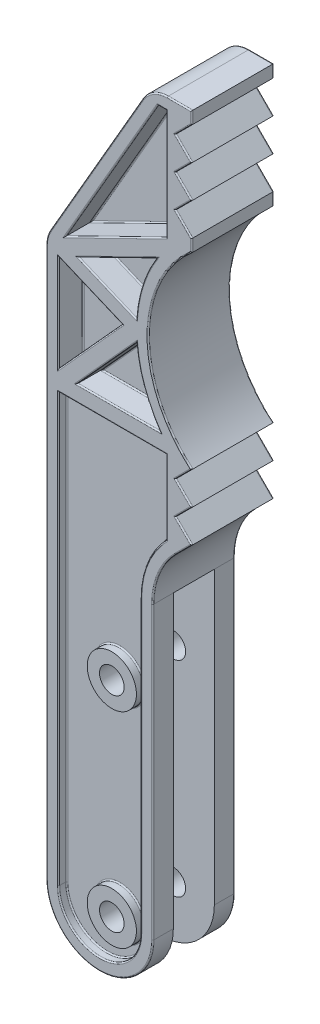
SolidWorks part; units mm, degrees
material "AISI 1020"
ref_plane "Front Plane" through (0, 0, 0) normal (0, 0, 1) x (1, 0, 0)
ref_plane "Top Plane" through (0, 0, 0) normal (0, 1, 0) x (1, 0, 0)
ref_plane "Right Plane" through (0, 0, 0) normal (1, 0, 0) x (0, 0, -1)
sketch "Sketch1" plane through (0, 0, 0) normal (0, 0, 1) x (1, 0, 0)
  line L0 (0, 0) -> (0, 90) construction
  line L1 (0, 90) -> (-5, 90) construction
  line L2 (-5, 90) -> (-17.75, 67.9164) construction
  line L3 (-17.75, 67.9164) -> (-17.75, 0) construction
  line L4 (-17.75, 0) -> (0, 0) construction
  line L5 (-2, 90) -> (-2, 75) construction
  line L6 (-2, 75) -> (0, 75) construction
  line L7 (0, 88.5) -> (-2, 86.5)
  line L8 (-2, 86.5) -> (0, 84.5)
  line L9 (0, 84.5) -> (-2, 82.5)
  line L10 (-2, 82.5) -> (0, 80.5)
  line L11 (0, 80.5) -> (-2, 78.5)
  line L12 (-2, 78.5) -> (0, 76.5)
  line L13 (-17.75, 64.3) -> (0, 64.3) construction
  line L14 (-9.75, 0) -> (-9.75, 25) construction
  line L15 (-2, 42.1) -> (0, 44.1)
  line L16 (0, 44.1) -> (-2, 46.1)
  line L17 (-2, 46.1) -> (0, 48.1)
  line L18 (0, 48.1) -> (-2, 50.1)
  line L19 (-2, 50.1) -> (0, 52.1)
  line L20 (0, 88.5) -> (0, 90)
  line L21 (0, 90) -> (-5, 90)
  line L22 (0, 76.5) -> (0, 75)
  line L23 (-5, 90) -> (-17.75, 67.9164)
  line L24 (-17.75, 67.9164) -> (-17.75, 0)
  line L25 (-4.75, 0) -> (-4.75, 35.4609)
  arc A0 (0, 75) -> (0, 52.1) centre (9.6901, 63.55) ccw
  arc A1 (-17.75, 0) -> (-4.75, 0) centre (-11.25, 0) ccw
  arc A2 (-2, 42.1) -> (-4.75, 35.4609) centre (4.6391, 35.4609) ccw
  circle A3 centre (-9.75, 0) radius 1.5
  circle A4 centre (-9.75, 25) radius 1.5
  dimension "D11" = 15
  dimension "D12" = 6.5
  dimension "D13" = 3
  dimension "D1" = 90
  dimension "D2" = 30
  dimension "D3" = 5
  dimension "D4" = 17.75
  dimension "D5" = 2
  dimension "D6" = 15
  dimension "D7" = 1.5
  dimension "D8" = 3.5
  dimension "D10" = 24.2
  dimension "D14" = 5
  dimension "D15" = 25
  dimension "D9" = 3
extrude "Boss-Extrude1" add sketch "Sketch1" along normal mid plane 10
sketch "Sketch2" plane through (0, 0, 0) normal (0, 0, 1) x (1, 0, 0)
  line L0 (-15, -8.4108) -> (-15, 23.5892)
  line L1 (-4.75, 0) -> (-4.75, 35.4609) construction
  line L2 (-4.75, 0) -> (-4.75, -8.4108)
  line L3 (-4.75, -8.4108) -> (-15, -8.4108)
  line L4 (-4.75, 0) -> (-4.75, 35.4609)
  arc A0 (-15, 23.5892) -> (-4.75, 35.4609) centre (-3, 23.5892) cw
  dimension "D2" = 12
  dimension "D1" = 10.25
  dimension "D3" = 32
extrude "Cut-Extrude1" cut sketch "Sketch2" against normal mid plane 5
sketch "Sketch3" plane through (0, 0, 5) normal (0, 0, 1) x (1, 0, 0)
  line L0 (-3.1276, 88.5) -> (-3.1276, 43.0931)
  line L34 (-2.1213, 88.5) -> (-4.134, 88.5)
  line L35 (-4.134, 88.5) -> (-16.25, 67.5144)
  line L36 (-16.25, 67.5144) -> (-16.25, 0)
  line L37 (-6.25, 0) -> (-6.25, 35.4609)
  line L38 (-3.0607, 43.1607) -> (-2.1213, 44.1)
  line L39 (-2.1213, 44.1) -> (-4.1213, 46.1)
  line L40 (-4.1213, 46.1) -> (-2.1213, 48.1)
  line L41 (-2.1213, 48.1) -> (-4.1213, 50.1)
  line L42 (-4.1213, 50.1) -> (-2.1565, 52.0648)
  line L43 (-1.5, 75.6757) -> (-1.5, 75.8787)
  line L44 (-1.5, 75.8787) -> (-4.1213, 78.5)
  line L45 (-4.1213, 78.5) -> (-2.1213, 80.5)
  line L46 (-2.1213, 80.5) -> (-4.1213, 82.5)
  line L47 (-4.1213, 82.5) -> (-2.1213, 84.5)
  line L48 (-2.1213, 84.5) -> (-4.1213, 86.5)
  line L49 (-4.1213, 86.5) -> (-2.1213, 88.5)
  line L50 (-2.1213, 88.5) -> (-4.134, 88.5)
  line L51 (-4.134, 88.5) -> (-16.25, 67.5144)
  line L52 (-16.25, 67.5144) -> (-16.25, 0)
  line L53 (-6.25, 0) -> (-6.25, 35.4609)
  line L54 (-3.0607, 43.1607) -> (-2.1213, 44.1) construction
  line L55 (-2.1213, 44.1) -> (-4.1213, 46.1) construction
  line L56 (-4.1213, 46.1) -> (-2.1213, 48.1) construction
  line L57 (-2.1213, 48.1) -> (-4.1213, 50.1) construction
  line L58 (-4.1213, 50.1) -> (-2.1565, 52.0648) construction
  line L59 (-1.5, 75.6757) -> (-1.5, 75.8787) construction
  line L60 (-1.5, 75.8787) -> (-4.1213, 78.5) construction
  line L61 (-4.1213, 78.5) -> (-2.1213, 80.5) construction
  line L62 (-2.1213, 80.5) -> (-4.1213, 82.5) construction
  line L63 (-4.1213, 82.5) -> (-2.1213, 84.5) construction
  line L64 (-2.1213, 84.5) -> (-4.1213, 86.5) construction
  line L65 (-4.1213, 86.5) -> (-2.1213, 88.5) construction
  arc A6 (-16.25, 0) -> (-6.25, 0) centre (-11.25, 0) ccw
  arc A7 (-3.0607, 43.1607) -> (-6.25, 35.4609) centre (4.6391, 35.4609) ccw
  arc A8 (-1.5, 75.6757) -> (-2.1565, 52.0648) centre (9.6901, 63.55) ccw
  arc A9 (-16.25, 0) -> (-6.25, 0) centre (-11.25, 0) ccw
  arc A10 (-3.0607, 43.1607) -> (-6.25, 35.4609) centre (4.6391, 35.4609) ccw
  arc A11 (-1.5, 75.6757) -> (-2.1565, 52.0648) centre (9.6901, 63.55) ccw
  circle M20 centre (-9.75, 0) radius 1.5
  circle M41 centre (-9.75, 25) radius 1.5
  dimension "D1" = 1.5
extrude "Cut-Extrude2" cut sketch "Sketch3" against normal blind 1 contours A11 L0 L50 L51 L52 A9 L53 A10 M41 M20
sketch "Sketch4" plane through (0, 0, 4) normal (0, 0, 1) x (1, 0, 0)
  circle A0 centre (-9.75, 25) radius 1.5 construction
  circle A1 centre (-9.75, 25) radius 1.5
  circle A2 centre (-9.75, 0) radius 1.5 construction
  circle A3 centre (-9.75, 0) radius 1.5
extrude "Extrude-Thin1" add sketch "Sketch4" along normal blind 1 thin
sketch "Sketch5" plane through (0, 0, 4) normal (0, 0, 1) x (1, 0, 0)
  line L6 (-3.1276, 53.1598) -> (-16.25, 53.1598)
  line L12 (-3.1276, 73.9402) -> (-3.1276, 88.5)
  line L13 (-3.1276, 88.5) -> (-4.134, 88.5)
  line L14 (-4.134, 88.5) -> (-16.25, 67.5144)
  line L15 (-16.25, 67.5144) -> (-16.25, 0)
  line L16 (-6.25, 0) -> (-6.25, 35.4609)
  line L17 (-3.1276, 43.0931) -> (-3.1276, 53.1598)
  line L18 (-3.1276, 73.9402) -> (-3.1276, 88.5)
  line L19 (-3.1276, 88.5) -> (-4.134, 88.5)
  line L20 (-4.134, 88.5) -> (-16.25, 67.5144)
  line L21 (-16.25, 67.5144) -> (-16.25, 0)
  line L22 (-6.25, 0) -> (-6.25, 35.4609) construction
  line L23 (-3.1276, 43.0931) -> (-3.1276, 53.1598) construction
  arc A6 (-3.1276, 73.9402) -> (-3.1276, 53.1598) centre (9.6901, 63.55) ccw
  arc A7 (-16.25, 0) -> (-6.25, 0) centre (-11.25, 0) ccw
  arc A8 (-3.1276, 43.0931) -> (-6.25, 35.4609) centre (4.6391, 35.4609) ccw
  arc A9 (-3.1276, 73.9402) -> (-3.1276, 53.1598) centre (9.6901, 63.55) ccw
  arc A10 (-16.25, 0) -> (-6.25, 0) centre (-11.25, 0) ccw construction
  arc A11 (-3.1276, 43.0931) -> (-6.25, 35.4609) centre (4.6391, 35.4609) ccw construction
  arc M11 (-3.1276, 53.1598) -> (-3.1276, 73.9402) centre (9.6901, 63.55) cw
  line M12 (-3.1276, 73.9402) -> (-3.1276, 88.5)
  line M13 (-3.1276, 88.5) -> (-4.134, 88.5)
  line M14 (-4.134, 88.5) -> (-16.25, 67.5144)
  line M15 (-16.25, 67.5144) -> (-16.25, 0)
  dimension "D1" = 0
extrude "Cut-Extrude3" cut sketch "Sketch5" against normal blind 2 contours L6 M11 M12 M13 M14 M15
sketch "Sketch7" plane through (0, 0, 5) normal (0, 0, 1) x (1, 0, 0)
  line L0 (-16.25, 53.1598) -> (-3.1276, 53.1598)
  line L1 (-16.25, 53.1598) -> (-6.8099, 63.55)
  line L2 (-6.8099, 63.55) -> (-16.25, 67.5144)
  line L3 (-16.25, 67.5144) -> (-3.1276, 73.9402)
  arc A0 (-3.1276, 73.9402) -> (-3.1276, 53.1598) centre (9.6901, 63.55) ccw construction
extrude "Extrude-Thin3" add sketch "Sketch7" against normal up to body separate body thin thin type mid plane wall 2
sketch "Sketch8" plane through (0, 0, 5) normal (0, 0, 1) x (1, 0, 0)
  line L0 (-3.5674, 74.8383) -> (-3.1276, 73.9402) construction
  line L1 (-3.5674, 74.8383) -> (-3.1276, 73.9402)
  line L2 (-3.5674, 74.8383) -> (-3.1276, 75.0536)
  line L3 (-15.3538, 69.0668) -> (-3.5674, 74.8383) construction
  line L4 (-3.1276, 88.5) -> (-3.1276, 73.9402) construction
  line L5 (-3.1276, 75.0536) -> (-3.1276, 73.9402)
extrude "Boss-Extrude2" add sketch "Sketch8" against normal up to surface (3 mm away) up to face at (-5.8621, 78.969, 2)
mirror "Mirror2" about plane through (0, 0, 0) normal (0, 0, 1) of "Extrude-Thin3", "Boss-Extrude2", "Cut-Extrude3", "Extrude-Thin1", "Cut-Extrude2"
fillet "Fillet1" radius 3.5 2 edges at (-5, 90, 0) (-17.75, 67.9164, 0)
fillet "Fillet2" radius 0.15 124 edges at (-6.75, 25, 4) (-6.75, 0, 4) (-11.25, -6.5, 5) (-9.7439, 78.7834, 2) (-3.6308, 88.5, 2) (-5.8333, 57.9576, 2) (-6.0258, 68.576, 2) (-16.25, 60.5384, 2) (-4.75, 17.7305, 5) (-16.25, 60.5384, 5) (-16.25, 26.0799, 5) (-16.25, 26.0799, 4) (-3.1276, 47.6264, 5) (-3.1276, 47.6264, 4) (-6.0258, 68.576, 5) (-5.8333, 57.9576, 5) (-9.0871, 69.9085, 2) (-10.3044, 66.1021, 2) (-10.3695, 58.145, 2) (-8.9338, 54.1598, 2) (-9.6888, 52.1598, 4) (0, 89.25, -5) (-9.6888, 52.1598, 5) (-12.3756, 58.9113, 2) (-12.3756, 58.9113, 5) (-12.3756, 64.8027, 2) (-12.3756, 64.8027, 5) (-9.2407, 72.0602, 5) (-9.2407, 72.0602, 2) (-8.9338, 54.1598, 5) (-10.3695, 58.145, 5) (-10.3044, 66.1021, 5) (-9.0871, 69.9085, 5) (-1, 87.5, -5) (-1, 85.5, -5) (-1, 83.5, -5) (-1, 81.5, -5) (-4.0353, 39.054, 5) (-1, 79.5, -5) (-1, 77.5, -5) (0, 75.75, -5) (-5.3099, 63.55, -5) (-3.1276, 81.7768, 2) (-1, 51.1, -5) (-1, 49.1, -5) (-1, 47.1, -5) (-1, 43.1, 5) (-1, 45.1, -5) (-3.6308, 88.5, -5) (-9.7439, 78.7834, -5) (-11.25, -5, -5) (-1, 43.1, -5) (-6.25, 17.7305, -5) (-5.4392, 39.584, -4) (-11.25, -5, -4) (-6.25, 17.7305, -4) (-4.0353, 39.054, -5) (-5.4392, 39.584, -5) (-3.1276, 81.7768, -5) (-4.75, 17.7305, -5) (-11.25, -6.5, -5) (-12.75, 25, -4) (-1.4896, 90, -5) (-1, 45.1, 5) (-12.75, 0, -4) (-3.6308, 88.5, -2) (-9.7439, 78.7834, -2) (-16.25, 60.5384, -2) (-1, 47.1, 5) (-5.8333, 57.9576, -2) (-6.0258, 68.576, -2) (-3.1276, 47.6264, -4) (-16.25, 26.0799, -4) (-3.1276, 47.6264, -5) (-16.25, 60.5384, -5) (-16.25, 26.0799, -5) (-6.0258, 68.576, -5) (-5.8333, 57.9576, -5) (-9.2407, 72.0602, -2) (-12.3756, 64.8027, -2) (-12.3756, 58.9113, -2) (-9.6888, 52.1598, -4) (-8.9338, 54.1598, -2) (-8.9338, 54.1598, -5) (-10.3695, 58.145, -2) (-10.3695, 58.145, -5) (-10.3044, 66.1021, -2) (-10.3044, 66.1021, -5) (-9.0871, 69.9085, -2) (-9.0871, 69.9085, -5) (-9.6888, 52.1598, -5) (-12.3756, 58.9113, -5) (-12.3756, 64.8027, -5) (-9.2407, 72.0602, -5) (-1, 49.1, 5) (-3.1276, 81.7768, -2) (-1, 51.1, 5) (-11.6457, 78.4893, -5) (-11.6457, 78.4893, 5) (-17.75, 33.4893, -5) (-17.6307, 67.8844, -5) (-4.7293, 89.5311, -5) (-17.75, 33.4893, 5) (-17.6307, 67.8844, 5) (-4.7293, 89.5311, 5) (-5.3099, 63.55, 5) (-1.4896, 90, 5) (0, 75.75, 5) (-1, 77.5, 5) (-1, 79.5, 5) (-1, 81.5, 5) (-1, 83.5, 5) (-1, 85.5, 5) (-1, 87.5, 5) (0, 89.25, 5) (-5.4392, 39.584, 5) (-6.25, 17.7305, 4) (-11.25, -5, 4) (-3.1276, 81.7768, 5) (-5.4392, 39.584, 4) (-3.6308, 88.5, 5) (-9.7439, 78.7834, 5) (-11.25, -5, 5) (-6.25, 17.7305, 5)
